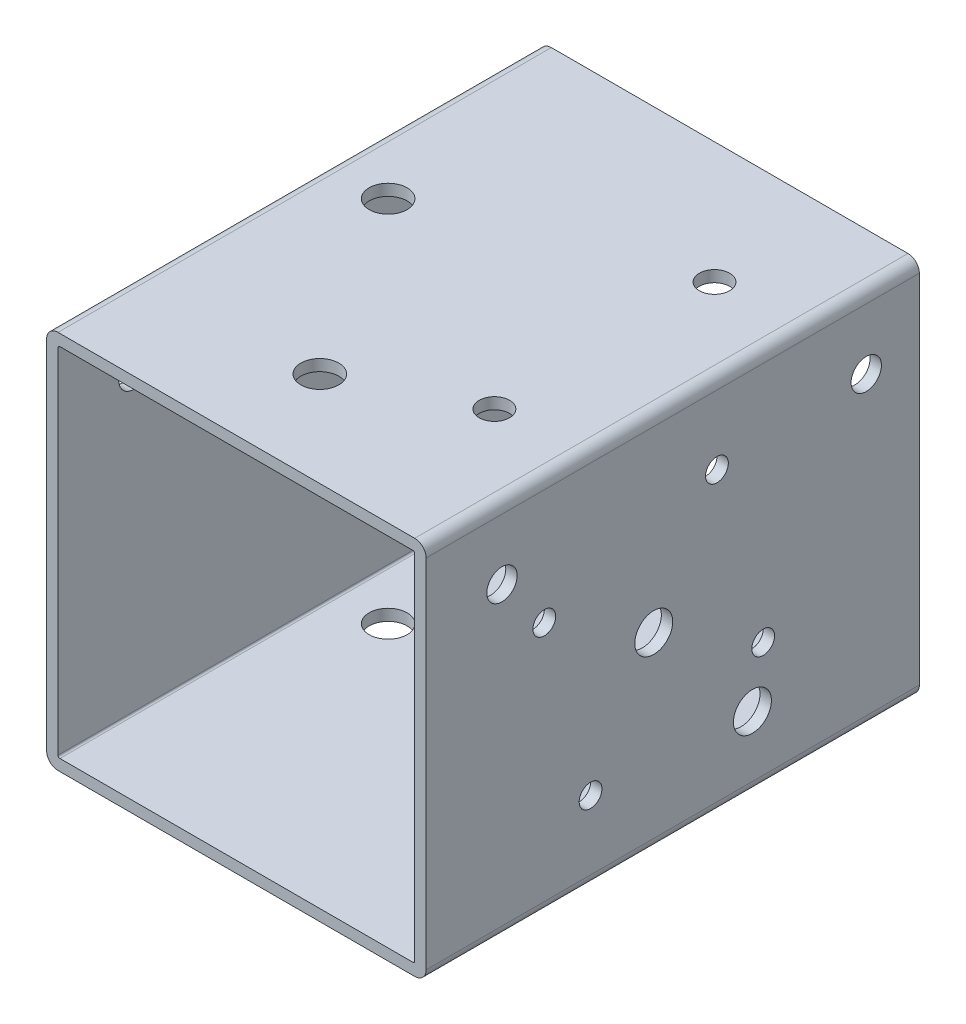
SolidWorks part; units mm, degrees
ref_plane "Front Plane" through (0, 0, 0) normal (0, 0, 1) x (1, 0, 0)
ref_plane "Top Plane" through (0, 0, 0) normal (0, 1, 0) x (1, 0, 0)
ref_plane "Right Plane" through (0, 0, 0) normal (1, 0, 0) x (0, 0, -1)
sketch "Sketch1" plane through (0, 0, 0) normal (0, 0, 1) x (1, 0, 0)
  line L1 (-50, 50) -> (50, 50)
  line L2 (-50, 50) -> (-50, -50)
  line L3 (-50, -50) -> (50, -50)
  line L4 (50, 50) -> (50, -50)
  line L5 (-50, 50) -> (50, -50) construction
  line L6 (-50, -50) -> (50, 50) construction
  point P0 (0, 0)
  dimension "D1" = 100
  dimension "D2" = 100
extrude "Extrude-Thin1" add sketch "Sketch1" along normal blind 130 thin
fillet "Fillet1" radius 0.5 4 edges at (-47, -47, 65) (-47, 47, 65) (47, 47, 65) (47, -47, 65)
fillet "Fillet2" radius 3 4 edges at (50, -50, 65) (-50, -50, 65) (50, 50, 65) (-50, 50, 65)
sketch "Holes - top" plane through (0, 0, 0) normal (0, 1, 0) x (1, 0, 0)
  line L0 (-3, 0) -> (-3, -130) construction
  line L1 (47, -130) -> (-47, -130) construction
  line L2 (-23, 0) -> (-23, -130) construction
  line L3 (47, 0) -> (-47, 0) construction
  line L4 (17, 0) -> (17, -130) construction
  circle A0 centre (-34, -56) radius 11 construction
  circle A1 centre (28, -90) radius 11 construction
  circle A2 centre (28, -32) radius 11 construction
  dimension "D4" = 22
  dimension "D1" = 40
  dimension "D2" = 40
  dimension "D3" = 32
  dimension "D5" = 56
  dimension "D6" = 3
hole_wizard "Ø8.0 (8) Diameter Hole2" positions "Sketch6" profile "Sketch5" hole size "Ø8.0" standard "ANSI Metric" end condition through all
sketch "Sketch6" plane through (0, 50, 0) normal (0, 1, 0) x (1, 0, 0)
  point P0 (28, -32)
  point P6 (28, -90)
sketch "Sketch5" plane through (28, 50, 32) normal (1, 0, 0) x (0, 0, 1)
  line L0 (0, 0) -> (0, 100)
  line L1 (0, 100) -> (4, 100)
  line L2 (4, 100) -> (4, 0)
  line L5 (4, 0) -> (0, 0)
  line L11 (0, -6.35) -> (0, 107.95) construction
  dimension "Thru Hole Dia." = 8
  dimension "Thru Hole Depth" = 100
sketch "Holes - side" plane through (0, 0, 0) normal (1, 0, 0) x (0, 0, -1)
  line L0 (0, 0) -> (-130, 0) construction
  line L1 (-130, -47) -> (-130, 47) construction
  line L2 (-130, 20) -> (0, 20) construction
  line L3 (0, -47) -> (0, 47) construction
  line L4 (-130, -20) -> (0, -20) construction
  circle A0 centre (-110, 31) radius 11 construction
  circle A1 centre (-14, 31) radius 11 construction
  circle A2 centre (-44, -31) radius 11 construction
  dimension "D1" = 40
  dimension "D2" = 22
  dimension "D3" = 20
  dimension "D4" = 14
  dimension "D5" = 44
hole_wizard "Ø8.0 (8) Diameter Hole3" positions "Sketch9" profile "Sketch8" hole size "Ø8.0" standard "ANSI Metric" end condition through all
sketch "Sketch9" plane through (50, 0, 0) normal (1, 0, 0) x (0, 0, -1)
  point P0 (-14, 31)
  point P3 (-110, 31)
sketch "Sketch8" plane through (50, 31, 14) normal (0, 1, 0) x (0, 0, -1)
  line L0 (0, 0) -> (0, 100)
  line L1 (0, 100) -> (4, 100)
  line L2 (4, 100) -> (4, 0)
  line L5 (4, 0) -> (0, 0)
  line L11 (0, -6.35) -> (0, 107.95) construction
  dimension "Thru Hole Dia." = 8
  dimension "Thru Hole Depth" = 100
hole_wizard "Ø10.0 (10) Diameter Hole1" positions "Sketch12" profile "Sketch11" hole size "Ø10.0" standard "ANSI Metric" end condition through all
sketch "Sketch12" plane through (0, 50, 0) normal (0, 1, 0) x (1, 0, 0)
  point P0 (-34, -56)
sketch "Sketch11" plane through (-34, 50, 56) normal (1, 0, 0) x (0, 0, 1)
  line L0 (0, 0) -> (0, 100)
  line L1 (0, 100) -> (5, 100)
  line L2 (5, 100) -> (5, 0)
  line L5 (5, 0) -> (0, 0)
  line L11 (0, -6.35) -> (0, 107.95) construction
  dimension "Thru Hole Dia." = 10
  dimension "Thru Hole Depth" = 100
hole_wizard "Ø10.0 (10) Diameter Hole2" positions "Sketch14" profile "Sketch13" hole size "Ø10.0" standard "ANSI Metric" end condition through all
sketch "Sketch14" plane through (50, 0, 0) normal (1, 0, 0) x (0, 0, -1)
  point P0 (-44, -31)
sketch "Sketch13" plane through (50, -31, 44) normal (0, 1, 0) x (0, 0, -1)
  line L0 (0, 0) -> (0, 100)
  line L1 (0, 100) -> (5, 100)
  line L2 (5, 100) -> (5, 0)
  line L5 (5, 0) -> (0, 0)
  line L11 (0, -6.35) -> (0, 107.95) construction
  dimension "Thru Hole Dia." = 10
  dimension "Thru Hole Depth" = 100
hole_wizard "M8x1.25 Tapped Hole1" positions "Sketch18" profile "Sketch17" tap size "M8x1.25" standard "ANSI Metric"
sketch "Sketch18" plane through (-50, 0, 0) normal (-1, 0, 0) x (0, 0, 1)
  line L0 (56, 35) -> (56, -15) construction
  point P0 (56, -15)
  point P2 (56, 35)
  dimension "D1" = 56
  dimension "D2" = 35
  dimension "D3" = 15
sketch "Sketch17" plane through (-50, -15, 56) normal (0, 1, 0) x (0, 0, 1)
  line L0 (0, 0) -> (0, 3)
  line L1 (0, 3) -> (3.4, 3)
  line L2 (3.4, 3) -> (3.4, 0)
  line L5 (3.4, 0) -> (0, 0)
  line L11 (0, -6.35) -> (0, 107.95) construction
  dimension "Thru Tap Drill Dia." = 6.8
  dimension "Thru Tap Drill Depth" = 3
cosmetic thread "Hole Thread1" parameters "D2"=8
cosmetic thread "Hole Thread2" parameters "D2"=8
hole_wizard "M8x1.25 Tapped Hole2" positions "Sketch21" profile "Sketch20" tap size "M8x1.25" standard "ANSI Metric"
sketch "Sketch21" plane through (0, -50, 0) normal (0, -1, 0) x (-1, 0, 0)
  line L0 (20, -44) -> (-35, -44) construction
  point P0 (20, -44)
  point P2 (-35, -44)
  dimension "D1" = 44
  dimension "D2" = 35
  dimension "D3" = 20
sketch "Sketch20" plane through (-20, -50, 44) normal (1, 0, 0) x (0, 0, -1)
  line L0 (0, 0) -> (0, 3)
  line L1 (0, 3) -> (3.4, 3)
  line L2 (3.4, 3) -> (3.4, 0)
  line L5 (3.4, 0) -> (0, 0)
  line L11 (0, -6.35) -> (0, 107.95) construction
  dimension "Thru Tap Drill Dia." = 6.8
  dimension "Thru Tap Drill Depth" = 3
cosmetic thread "Hole Thread3" parameters "D2"=8
cosmetic thread "Hole Thread4" parameters "D2"=8
sketch "Holes - Nema 23 motor" plane through (0, 0, 0) normal (1, 0, 0) x (0, 0, -1)
  line L0 (-98.8427, 16.6524) -> (-53.3476, 28.8427) construction
  line L1 (-98.8427, 16.6524) -> (-86.6524, -28.8427) construction
  line L2 (-53.3476, 28.8427) -> (-41.1573, -16.6524) construction
  line L3 (-86.6524, -28.8427) -> (-41.1573, -16.6524) construction
  line L4 (-98.8427, 16.6524) -> (-41.1573, -16.6524) construction
  line L5 (-53.3476, 28.8427) -> (-86.6524, -28.8427) construction
  line L6 (0, 0) -> (-130, 0) construction
  point P1 (-70, 0)
  dimension "D1" = 70
  dimension "D2" = 47.1
  dimension "D3" = 47.1
  dimension "D4" = 15
hole_wizard "Ø10.0 (10) Diameter Hole3" positions "Sketch24" profile "Sketch23" hole size "Ø10.0" standard "ANSI Metric"
sketch "Sketch24" plane through (50, 0, 0) normal (1, 0, 0) x (0, 0, -1)
  point P0 (-70, 0)
sketch "Sketch23" plane through (50, 0, 70) normal (0, 1, 0) x (0, 0, -1)
  line L0 (0, 0) -> (0, 3)
  line L1 (0, 3) -> (5, 3)
  line L2 (5, 3) -> (5, 0)
  line L5 (5, 0) -> (0, 0)
  line L11 (0, -6.35) -> (0, 107.95) construction
  dimension "Thru Hole Dia." = 10
  dimension "Thru Hole Depth" = 3
hole_wizard "Ø6.0 (6) Diameter Hole1" positions "Sketch26" profile "Sketch25" hole size "Ø6.0" standard "ANSI Metric"
sketch "Sketch26" plane through (50, 0, 0) normal (1, 0, 0) x (0, 0, -1)
  point P0 (-41.1573, -16.6524)
  point P3 (-53.3476, 28.8427)
  point P6 (-98.8427, 16.6524)
  point P9 (-86.6524, -28.8427)
sketch "Sketch25" plane through (50, -16.6524, 41.1573) normal (0, 1, 0) x (0, 0, -1)
  line L0 (0, 0) -> (0, 3)
  line L1 (0, 3) -> (3, 3)
  line L2 (3, 3) -> (3, 0)
  line L5 (3, 0) -> (0, 0)
  line L11 (0, -6.35) -> (0, 107.95) construction
  dimension "Thru Hole Dia." = 6
  dimension "Thru Hole Depth" = 3
hole_wizard "Ø10.0 (10) Diameter Hole4" positions "Sketch29" profile "Sketch28" hole size "Ø10.0" standard "ANSI Metric"
sketch "Sketch29" plane through (0, 50, 0) normal (0, 1, 0) x (1, 0, 0)
  line L0 (-3, 0) -> (-3, -130) construction
  point P0 (-3, -105)
  dimension "D1" = 15
sketch "Sketch28" plane through (-3, 50, 105) normal (1, 0, 0) x (0, 0, 1)
  line L0 (0, 0) -> (0, 3)
  line L1 (0, 3) -> (5, 3)
  line L2 (5, 3) -> (5, 0)
  line L5 (5, 0) -> (0, 0)
  line L11 (0, -6.35) -> (0, 107.95) construction
  dimension "Thru Hole Dia." = 10
  dimension "Thru Hole Depth" = 3
sketch "Sketch32" plane through (50, 0, 0) normal (1, 0, 0) x (0, 0, -1)
  line L1 (0, -47) -> (0, 47) construction
  line L2 (-65, 69.5535) -> (-65, -72.7704) construction
  line L3 (-130, -47) -> (-130, 47) construction
  line L4 (-130, 50) -> (0, 50) construction
  circle A0 centre (-5, 13) radius 2
  circle A1 centre (-5, 4) radius 2
  circle A2 centre (-125, 4) radius 2
  circle A3 centre (-125, 13) radius 2
  dimension "D1" = 46
  dimension "D2" = 9
  dimension "D3" = 4
  dimension "D5" = 5
  dimension "D4" = 0
  dimension "D6" = 65
equation "\"a\"= \"Trolley Profile@Plasma Beta.Assembly\""
equation "\"b\"= \"Trolley Profile Thickness@Plasma Beta.Assembly\""
equation "\"L\"= 130"
equation "\"D2@Sketch1\"=\"a\""
equation "\"D1@Sketch1\"=\"a\""
equation "\"D1@Extrude-Thin1\"=\"L\""
equation "\"D5@Extrude-Thin1\"=\"b\""
equation "\"D1@Fillet2\"=\"b\""
equation "\"d-bearing\"= 22'diameter of bearing"
equation "\"a-small\"= \"Beam Profile@Plasma Beta.Assembly\"'profile of smaller beam"
equation "\"D4@Holes - top\"=\"d-bearing\""
equation "\"D2@Holes - side\"=\"d-bearing\""
equation "\"D1@Holes - top\"=\"a-small\""
equation "\"D1@Holes - side\"=\"a-small\""
